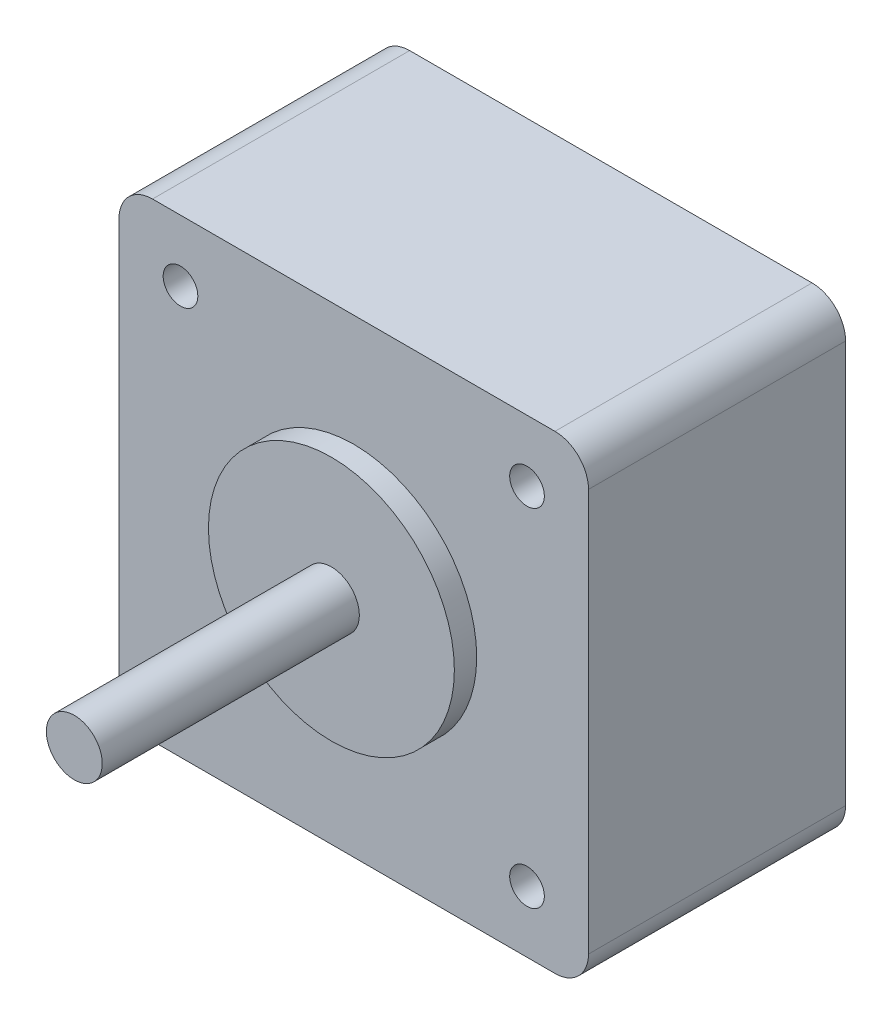
SolidWorks part; units mm, degrees
ref_plane "前视基准面" through (0, 0, 0) normal (0, 0, 1) x (1, 0, 0)
ref_plane "上视基准面" through (0, 0, 0) normal (0, 1, 0) x (1, 0, 0)
ref_plane "右视基准面" through (0, 0, 0) normal (1, 0, 0) x (0, 0, -1)
sketch "草图1" plane through (0, 0, 0) normal (0, 0, 1) x (1, 0, 0)
  line L1 (-18, 21) -> (18, 21)
  line L2 (-21, 18) -> (-21, -18)
  line L3 (-18, -21) -> (18, -21)
  line L4 (21, 18) -> (21, -18)
  line L5 (-21, 21) -> (21, -21) construction
  line L6 (-21, -21) -> (21, 21) construction
  arc A0 (-18, -21) -> (-21, -18) centre (-18, -18) cw
  arc A1 (21, -18) -> (18, -21) centre (18, -18) cw
  arc A2 (18, 21) -> (21, 18) centre (18, 18) cw
  arc A3 (-21, 18) -> (-18, 21) centre (-18, 18) cw
  point P0 (0, 0)
  dimension "D3" = 3
  dimension "D1" = 42
  dimension "D2" = 42
extrude "凸台-拉伸1" add sketch "草图1" along normal blind 23
ref_plane "基准面1" through (0, 0, 23) normal (0, 0, 1) x (1, 0, 0)
sketch "草图2" plane through (0, 0, 23) normal (0, 0, 1) x (1, 0, 0)
  circle A0 centre (0, 0) radius 11
  dimension "D1" = 22
extrude "凸台-拉伸2" add sketch "草图2" along normal blind 2
ref_plane "基准面2" through (0, 0, 25) normal (0, 0, 1) x (1, 0, 0)
sketch "草图3" plane through (0, 0, 25) normal (0, 0, 1) x (1, 0, 0)
  circle A0 centre (0, 0) radius 2.5
  dimension "D1" = 5
extrude "凸台-拉伸3" add sketch "草图3" along normal blind 23
sketch "草图4" plane through (0, 0, 23) normal (0, 0, 1) x (1, 0, 0)
  line L1 (-15.5, 15.5) -> (15.5, 15.5) construction
  line L2 (-15.5, 15.5) -> (-15.5, -15.5) construction
  line L3 (-15.5, -15.5) -> (15.5, -15.5) construction
  line L4 (15.5, 15.5) -> (15.5, -15.5) construction
  line L5 (-15.5, 15.5) -> (15.5, -15.5) construction
  line L6 (-15.5, -15.5) -> (15.5, 15.5) construction
  circle A0 centre (-15.5, 15.5) radius 1.55
  circle A1 centre (15.5, 15.5) radius 1.55
  circle A2 centre (15.5, -15.5) radius 1.55
  circle A3 centre (-15.5, -15.5) radius 1.55
  point P0 (0, 0)
  dimension "D3" = 3.1
  dimension "D4" = 3.1
  dimension "D5" = 3.1
  dimension "D6" = 3.1
  dimension "D1" = 31
  dimension "D2" = 31
extrude "切除-拉伸1" cut sketch "草图4" against normal blind 5
